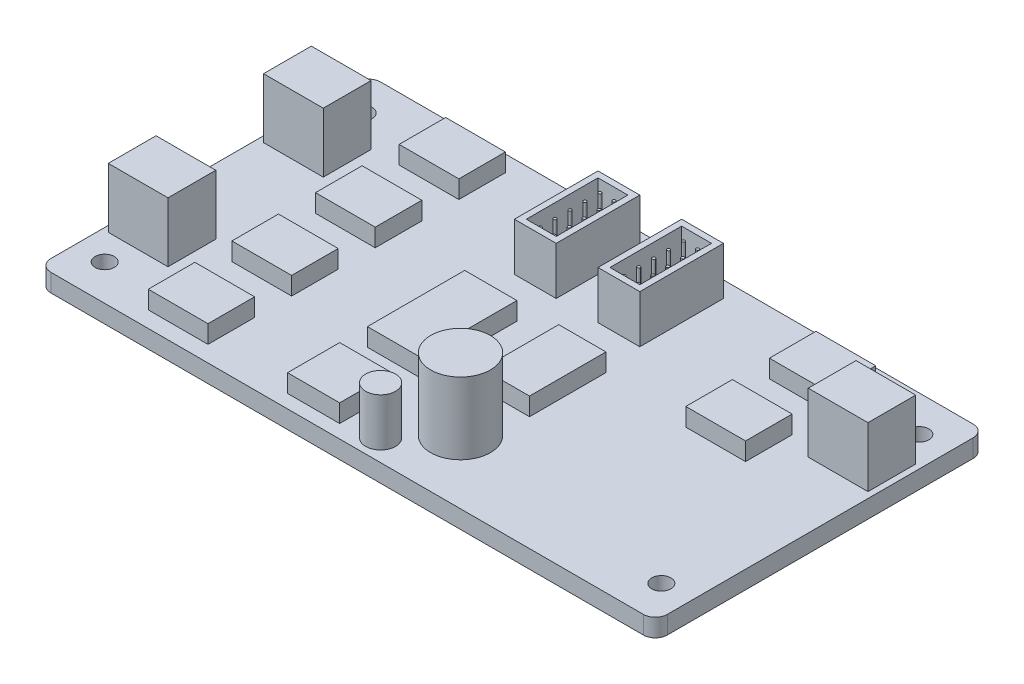
SolidWorks part; units mm, degrees
ref_plane "前视基准面" through (0, 0, 0) normal (0, 0, 1) x (1, 0, 0)
ref_plane "上视基准面" through (0, 0, 0) normal (0, 1, 0) x (1, 0, 0)
ref_plane "右视基准面" through (0, 0, 0) normal (1, 0, 0) x (0, 0, -1)
sketch "草图1" plane through (0, 0, 0) normal (0, 1, 0) x (1, 0, 0)
  line L1 (-51.6, -27.6) -> (51.6, -27.6)
  line L2 (-51.6, -27.6) -> (-51.6, 27.6)
  line L3 (-51.6, 27.6) -> (51.6, 27.6)
  line L4 (51.6, -27.6) -> (51.6, 27.6)
  line L5 (-51.6, -27.6) -> (51.6, 27.6) construction
  line L6 (-51.6, 27.6) -> (51.6, -27.6) construction
  circle A0 centre (-46.6, 21.6) radius 1.6
  circle A1 centre (46.6, 21.6) radius 1.6
  circle A2 centre (46.6, -21.6) radius 1.6
  circle A3 centre (-46.6, -21.6) radius 1.6
  point P0 (0, 0)
  dimension "D3" = 3.2
  dimension "D6" = 2
  dimension "D1" = 103.2
  dimension "D2" = 55.2
  dimension "D4" = 21.6
  dimension "D5" = 46.6
  dimension "D7" = 2
extrude "凸台-拉伸1" add sketch "草图1" along normal blind 3
fillet "圆角1" radius 2 4 edges at (-51.6, 1.5, -27.6) (51.6, 1.5, -27.6) (51.6, 1.5, 27.6) (-51.6, 1.5, 27.6)
sketch "草图2" plane through (0, 3, 0) normal (0, 1, 0) x (1, 0, 0)
  line L1 (-40.6, 9) -> (-50.6, 9)
  line L2 (-40.6, 9) -> (-40.6, 17)
  line L3 (-40.6, 17) -> (-50.6, 17)
  line L4 (-50.6, 9) -> (-50.6, 17)
  line L5 (-40.6, 9) -> (-50.6, 17) construction
  line L6 (-40.6, 17) -> (-50.6, 9) construction
  line L21 (-51.6, 25.6) -> (-51.6, -25.6) construction
  line L22 (50.6, 9) -> (50.6, 17)
  line L23 (50.6, 9) -> (40.6, 9)
  line L24 (40.6, 9) -> (40.6, 17)
  line L25 (50.6, 17) -> (40.6, 17)
  line L26 (50.6, -17) -> (50.6, -9)
  line L27 (50.6, -17) -> (40.6, -17)
  line L28 (40.6, -17) -> (40.6, -9)
  line L29 (50.6, -9) -> (40.6, -9)
  line L30 (-40.6, -17) -> (-40.6, -9)
  line L31 (-40.6, -17) -> (-50.6, -17)
  line L32 (-50.6, -17) -> (-50.6, -9)
  line L33 (-40.6, -9) -> (-50.6, -9)
  point P0 (-45.6, 13)
  dimension "D1" = 10
  dimension "D2" = 8
  dimension "D3" = 13
  dimension "D6" = 1
  dimension "D4" = 2
  dimension "D5" = 2
extrude "凸台-拉伸2" add sketch "草图2" along normal blind 10
sketch "草图3" plane through (0, 3, 0) normal (0, 1, 0) x (1, 0, 0)
  line L0 (26, 17.1) -> (26, 24.9)
  line L1 (-36, 17.1) -> (-26, 17.1)
  line L2 (-36, 17.1) -> (-36, 24.9)
  line L3 (-36, 24.9) -> (-26, 24.9)
  line L4 (-26, 17.1) -> (-26, 24.9)
  line L5 (-36, 17.1) -> (-26, 24.9) construction
  line L6 (-36, 24.9) -> (-26, 17.1) construction
  line L7 (26, 17.1) -> (36, 17.1)
  line L8 (36, 17.1) -> (36, 24.9)
  line L9 (26, 24.9) -> (36, 24.9)
  line L10 (26, 3.1) -> (26, 10.9)
  line L11 (26, 3.1) -> (36, 3.1)
  line L12 (36, 3.1) -> (36, 10.9)
  line L13 (26, 10.9) -> (36, 10.9)
  line L14 (26, -10.9) -> (26, -3.1)
  line L15 (26, -10.9) -> (36, -10.9)
  line L16 (36, -10.9) -> (36, -3.1)
  line L17 (26, -3.1) -> (36, -3.1)
  line L18 (26, -24.9) -> (26, -17.1)
  line L19 (26, -24.9) -> (36, -24.9)
  line L20 (36, -24.9) -> (36, -17.1)
  line L21 (26, -17.1) -> (36, -17.1)
  line L22 (-36, 3.1) -> (-36, 10.9)
  line L23 (-36, 3.1) -> (-26, 3.1)
  line L24 (-26, 3.1) -> (-26, 10.9)
  line L25 (-36, 10.9) -> (-26, 10.9)
  line L26 (-36, -10.9) -> (-36, -3.1)
  line L27 (-36, -10.9) -> (-26, -10.9)
  line L28 (-26, -10.9) -> (-26, -3.1)
  line L29 (-36, -3.1) -> (-26, -3.1)
  line L30 (-36, -24.9) -> (-36, -17.1)
  line L31 (-36, -24.9) -> (-26, -24.9)
  line L32 (-26, -24.9) -> (-26, -17.1)
  line L33 (-36, -17.1) -> (-26, -17.1)
  line L34 (-36, 17.1) -> (-36, 3.1) construction
  line L35 (0, 39.1571) -> (0, -33.1523) construction
  line L36 (3.5, -8.4771) -> (11.4073, -8.4771)
  line L37 (3.5, -8.4771) -> (3.5, 4.3213)
  line L38 (3.5, 4.3213) -> (11.4073, 4.3213)
  line L39 (11.4073, -8.4771) -> (11.4073, 4.3213)
  line L40 (3.5, -8.4771) -> (11.4073, 4.3213) construction
  line L41 (3.5, 4.3213) -> (11.4073, -8.4771) construction
  line L42 (-12.2356, -11.9771) -> (-3.5, -11.9771)
  line L43 (-12.2356, -11.9771) -> (-12.2356, 4.3213)
  line L44 (-12.2356, 4.3213) -> (-3.5, 4.3213)
  line L45 (-3.5, -11.9771) -> (-3.5, 4.3213)
  line L46 (-12.2356, -11.9771) -> (-3.5, 4.3213) construction
  line L47 (-12.2356, 4.3213) -> (-3.5, -11.9771) construction
  line L48 (-12.2356, -16.6172) -> (-3.5, -16.6172)
  line L49 (-12.2356, -16.6172) -> (-12.2356, -25.3528)
  line L50 (-12.2356, -25.3528) -> (-3.5, -25.3528)
  line L51 (-3.5, -16.6172) -> (-3.5, -25.3528)
  line L52 (-12.2356, -16.6172) -> (-3.5, -25.3528) construction
  line L53 (-12.2356, -25.3528) -> (-3.5, -16.6172) construction
  point P0 (-31, 21)
  point P5 (7.4537, -2.0779)
  point P41 (-7.8678, -3.8279)
  point P46 (-7.8678, -20.985)
  dimension "D1" = 10
  dimension "D2" = 7.8
  dimension "D3" = 21
  dimension "D4" = 31
  dimension "D7" = 14
  dimension "D8" = 3.5
  dimension "D9" = 3.5
  dimension "D5" = 2
  dimension "D6" = 4
extrude "凸台-拉伸3" add sketch "草图3" along normal blind 3
sketch "草图4" plane through (0, 3, 0) normal (0, 1, 0) x (1, 0, 0)
  line L1 (-10.5, 10.9) -> (-3.5, 10.9)
  line L2 (-10.5, 10.9) -> (-10.5, 24.9)
  line L3 (-10.5, 24.9) -> (-3.5, 24.9)
  line L4 (-3.5, 10.9) -> (-3.5, 24.9)
  line L5 (-10.5, 10.9) -> (-3.5, 24.9) construction
  line L6 (-10.5, 24.9) -> (-3.5, 10.9) construction
  line L7 (-26, 24.9) -> (-36, 24.9) construction
  line L8 (0, 29.7557) -> (0, -42.1132) construction
  line L9 (10.5, 24.9) -> (3.5, 24.9)
  line L10 (3.5, 10.9) -> (3.5, 24.9)
  line L11 (10.5, 10.9) -> (3.5, 10.9)
  line L12 (10.5, 10.9) -> (10.5, 24.9)
  line L13 (-3.5, -11.9771) -> (-3.5, 4.3213) construction
  line L14 (-4.5, 11.9) -> (-4.5, 23.9)
  line L15 (-9.5, 23.9) -> (-4.5, 23.9)
  line L16 (-9.5, 11.9) -> (-9.5, 23.9)
  line L17 (-9.5, 11.9) -> (-4.5, 11.9)
  line L18 (9.5, 11.9) -> (4.5, 11.9)
  line L19 (9.5, 11.9) -> (9.5, 23.9)
  line L20 (9.5, 23.9) -> (4.5, 23.9)
  line L21 (4.5, 11.9) -> (4.5, 23.9)
  line L22 (-7, 25.8889) -> (-7, 9.7019) construction
  circle A0 centre (2, -24) radius 2.5
  point P4 (-7, 17.9)
  dimension "D1" = 5
  dimension "D2" = 24
  dimension "D3" = 2
  dimension "D4" = 14
  dimension "D5" = 7
  dimension "D6" = 1
extrude "凸台-拉伸4" add sketch "草图4" along normal blind 8
sketch "草图5" plane through (0, 3, 0) normal (0, 1, 0) x (1, 0, 0)
  line L0 (-7, 23.2789) -> (-7, 12.1861) construction
  line L1 (-8.9974, 17.9) -> (-4.8864, 17.9) construction
  line L2 (0, 32.2015) -> (0, -34.1934) construction
  circle A0 centre (-8.1823, 22.9) radius 0.25
  circle A1 centre (-5.8177, 22.9) radius 0.25
  circle A2 centre (-8.1823, 20.4) radius 0.25
  circle A3 centre (-5.8177, 20.4) radius 0.25
  circle A4 centre (-8.1823, 17.9) radius 0.25
  circle A5 centre (-5.8177, 17.9) radius 0.25
  circle A6 centre (-8.1823, 15.4) radius 0.25
  circle A7 centre (-5.8177, 15.4) radius 0.25
  circle A8 centre (-8.1823, 12.9) radius 0.25
  circle A9 centre (-5.8177, 12.9) radius 0.25
  circle A10 centre (5.8177, 12.9) radius 0.25
  circle A11 centre (8.1823, 12.9) radius 0.25
  circle A12 centre (5.8177, 15.4) radius 0.25
  circle A13 centre (8.1823, 15.4) radius 0.25
  circle A14 centre (5.8177, 17.9) radius 0.25
  circle A15 centre (8.1823, 17.9) radius 0.25
  circle A16 centre (5.8177, 20.4) radius 0.25
  circle A17 centre (8.1823, 20.4) radius 0.25
  circle A18 centre (8.1823, 22.9) radius 0.25
  circle A19 centre (5.8177, 22.9) radius 0.25
  dimension "D1" = 0.5
  dimension "D2" = 5
extrude "凸台-拉伸5" add sketch "草图5" along normal blind 7
sketch "草图6" plane through (0, 3, 0) normal (0, 1, 0) x (1, 0, 0)
  circle A0 centre (8.3468, -16.9645) radius 5
  dimension "D1" = 10
extrude "凸台-拉伸6" add sketch "草图6" along normal blind 12
sketch "草图7" plane through (0, 3, 0) normal (0, 1, 0) x (1, 0, 0)
  line L1 (22.4258, -0.8814) -> (58.9564, -0.8814)
  line L2 (22.4258, -0.8814) -> (22.4258, -33.6106)
  line L3 (22.4258, -33.6106) -> (58.9564, -33.6106)
  line L4 (58.9564, -0.8814) -> (58.9564, -33.6106)
extrude "切除-拉伸1" cut sketch "草图7" along normal through all
